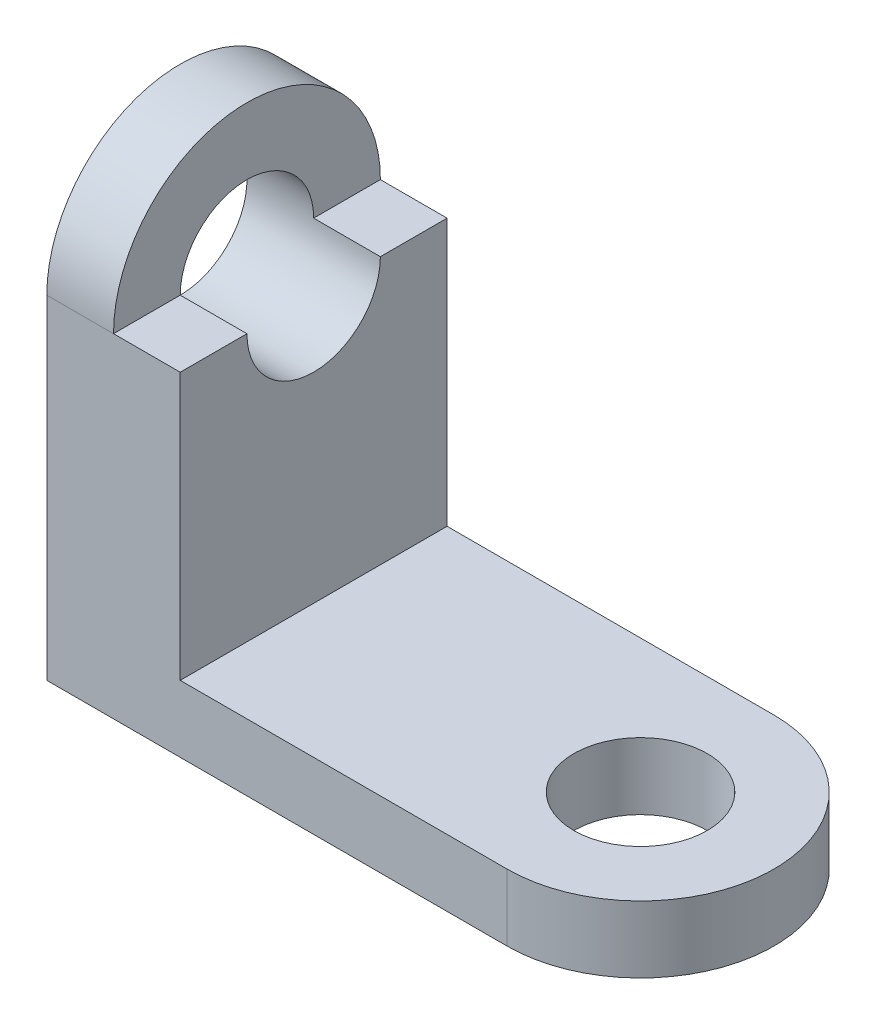
SolidWorks part; units mm, degrees
ref_plane "Front Plane" through (0, 0, 0) normal (0, 0, 1) x (1, 0, 0)
ref_plane "Top Plane" through (0, 0, 0) normal (0, 1, 0) x (1, 0, 0)
ref_plane "Right Plane" through (0, 0, 0) normal (1, 0, 0) x (0, 0, -1)
sketch "Sketch1" plane through (0, 0, 0) normal (0, 1, 0) x (1, 0, 0)
  line L0 (0, 0) -> (0, 1016)
  line L1 (0, 1016) -> (1752.6, 1016)
  line L2 (0, 0) -> (1752.6, 0)
  arc A0 (1752.6, 1016) -> (1752.6, 0) centre (1752.6, 508) cw
  circle A1 centre (1752.6, 508) radius 254
  dimension "D1" = 508
  dimension "D2" = 508
  dimension "D3" = 1752.6
extrude "Boss-Extrude1" add sketch "Sketch1" along normal blind 254
sketch "Sketch3" plane through (0, 0, 0) normal (-1, 0, 0) x (0, 0, 1)
  line L0 (-1016, 254) -> (-1016, 1270)
  line L1 (0, 254) -> (0, 1270)
  line L2 (-1016, 254) -> (0, 254) construction
  arc A0 (-1016, 1270) -> (0, 1270) centre (-508, 1270) cw
  circle A1 centre (-508, 1270) radius 254
  point P9 (-508, 1778)
  line M3 (0, 254) -> (-1016, 254)
  dimension "D1" = 508
  dimension "D2" = 1524
extrude "Boss-Extrude2" add sketch "Sketch3" against normal blind 254 contours A0 L0 L1 A1 M3
sketch "Sketch4" plane through (254, 0, 0) normal (1, 0, 0) x (0, 0, -1)
  line L0 (0, 1270) -> (254, 1270)
  line L1 (0, 1270) -> (0, 254)
  line L2 (0, 254) -> (1016, 254)
  line L3 (1016, 254) -> (1016, 1270)
  line L4 (1016, 1270) -> (762, 1270)
  circle A0 centre (508, 1270) radius 254 construction
  arc A1 (254, 1270) -> (762, 1270) centre (508, 1270) ccw
extrude "Boss-Extrude3" add sketch "Sketch4" along normal blind 254
